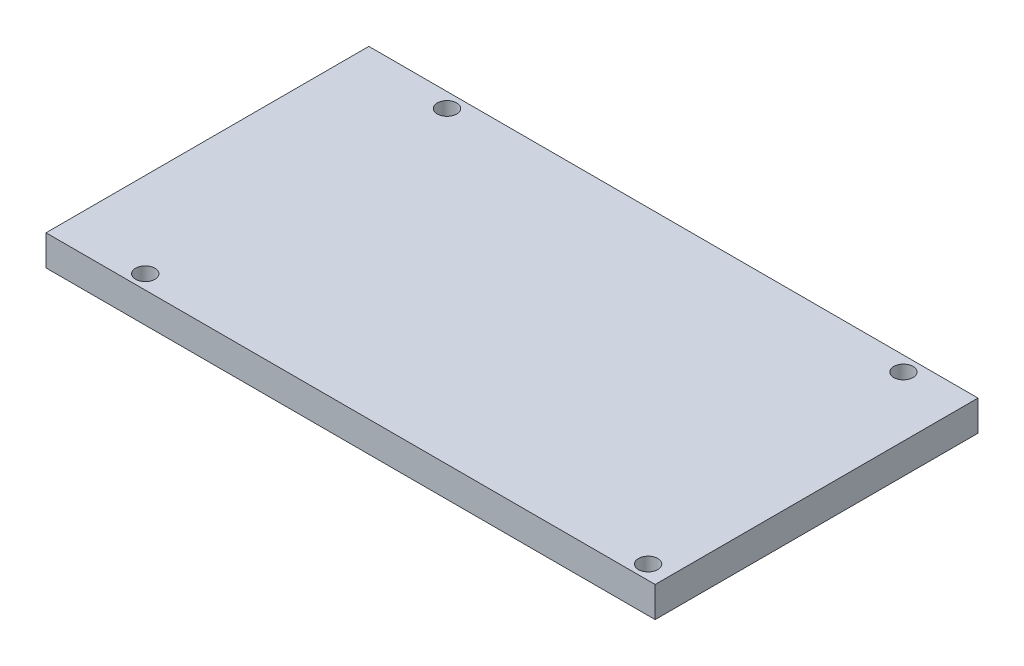
SolidWorks part; units mm, degrees
ref_plane "Front Plane" through (0, 0, 0) normal (0, 0, 1) x (1, 0, 0)
ref_plane "Top Plane" through (0, 0, 0) normal (0, 1, 0) x (1, 0, 0)
ref_plane "Right Plane" through (0, 0, 0) normal (1, 0, 0) x (0, 0, -1)
sketch "Sketch1" plane through (0, 0, 0) normal (0, 1, 0) x (1, 0, 0)
  line L1 (-50, -26.5) -> (50, -26.5)
  line L2 (-50, -26.5) -> (-50, 26.5)
  line L3 (-50, 26.5) -> (50, 26.5)
  line L4 (50, -26.5) -> (50, 26.5)
  line L5 (-50, -26.5) -> (50, 26.5) construction
  line L6 (-50, 26.5) -> (50, -26.5) construction
  point P0 (0, 0)
  dimension "D1" = 100
  dimension "D2" = 53
extrude "Boss-Extrude1" add sketch "Sketch1" along normal blind 5
sketch "Sketch2" plane through (0, 0, 0) normal (0, -1, 0) x (1, 0, 0)
  circle A0 centre (46.52, 24.173) radius 1.5875
  circle A1 centre (40.17, -24.087) radius 1.5875
  circle A2 centre (-34.76, -24.087) radius 1.5875
  circle A3 centre (-36.03, 24.173) radius 1.5875
extrude "Cut-Extrude1" cut sketch "Sketch2" against normal through all
